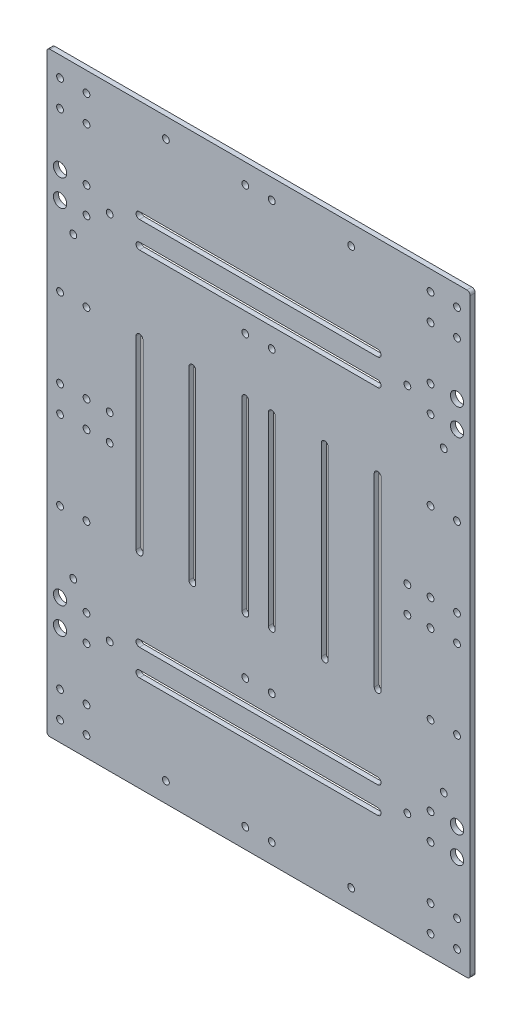
SolidWorks part; units mm, degrees
ref_plane "Front Plane" through (0, 0, 0) normal (0, 0, 1) x (1, 0, 0)
ref_plane "Top Plane" through (0, 0, 0) normal (0, 1, 0) x (1, 0, 0)
ref_plane "Right Plane" through (0, 0, 0) normal (1, 0, 0) x (0, 0, -1)
sketch "Sketch1" plane through (0, 0, 0) normal (0, 0, 1) x (1, 0, 0)
  line L1 (-128, -180) -> (128, -180)
  line L2 (-128, -180) -> (-128, 180)
  line L3 (-128, 180) -> (128, 180)
  line L4 (128, -180) -> (128, 180)
  line L5 (-128, -180) -> (128, 180) construction
  line L6 (-128, 180) -> (128, -180) construction
  point P0 (0, 0)
  dimension "D1" = 256
  dimension "D2" = 360
extrude "Boss-Extrude1" add sketch "Sketch1" along normal blind 3
fillet "Fillet1" radius 2 4 edges at (128, -180, 1.5) (-128, -180, 1.5) (-128, 180, 1.5) (128, 180, 1.5)
hole_wizard "Ø4.1 (4.1) Diameter Hole1" positions "Sketch3" profile "Sketch2" hole size "Ø4.1" standard "ANSI Metric" end condition through all
sketch "Sketch3" plane through (0, 0, 3) normal (0, 0, 1) x (1, 0, 0)
  point P0 (90, 8)
  point P2 (120, 8)
  point P4 (104, 8)
  point P9 (104, 56)
  point P11 (120, 56)
  point P13 (104, 104)
  point P15 (112, 90.15)
  point P17 (104, 120)
  point P19 (90, 112)
  point P21 (104, 152)
  point P23 (120, 152)
  point P25 (120, 168)
  point P27 (104, 168)
  point P37 (8, 168)
  point P39 (56, 168)
  point P47 (8, 90.15)
  dimension "D1" = 90
  dimension "D2" = 120
  dimension "D3" = 104
  dimension "D4" = 8
  dimension "D5" = 56
  dimension "D6" = 112
  dimension "D7" = 90.15
  dimension "D8" = 112
  dimension "D9" = 104
  dimension "D10" = 120
  dimension "D11" = 152
  dimension "D12" = 168
  dimension "D13" = 8
  dimension "D14" = 56
sketch "Sketch2" plane through (90, 8, 3) normal (1, 0, 0) x (0, -1, 0)
  line L0 (0, 0) -> (0, 3)
  line L1 (0, 3) -> (2.05, 3)
  line L2 (2.05, 3) -> (2.05, 0)
  line L5 (2.05, 0) -> (0, 0)
  line L11 (0, -6.35) -> (0, 107.95) construction
  dimension "Thru Hole Dia." = 4.1
  dimension "Thru Hole Depth" = 3
hole_wizard "Ø8.0 (8) Diameter Hole1" positions "Sketch5" profile "Sketch4" hole size "Ø8.0" standard "ANSI Metric" end condition through all
sketch "Sketch5" plane through (0, 0, 3) normal (0, 0, 1) x (1, 0, 0)
  point P0 (120, 120)
  point P2 (120, 104)
  dimension "D1" = 104
  dimension "D2" = 120
  dimension "D3" = 120
sketch "Sketch4" plane through (120, 120, 3) normal (1, 0, 0) x (0, -1, 0)
  line L0 (0, 0) -> (0, 3)
  line L1 (0, 3) -> (4, 3)
  line L2 (4, 3) -> (4, 0)
  line L5 (4, 0) -> (0, 0)
  line L11 (0, -6.35) -> (0, 107.95) construction
  dimension "Thru Hole Dia." = 8
  dimension "Thru Hole Depth" = 3
sketch "Sketch9" plane through (0, 0, 3) normal (0, 0, 1) x (1, 0, 0)
  line L0 (0, 104) -> (72, 104) construction
  line L1 (0, 106.05) -> (72, 106.05)
  line L2 (0, 101.95) -> (72, 101.95)
  line L3 (0, 120) -> (72, 120) construction
  line L4 (0, 122.05) -> (72, 122.05)
  line L5 (0, 117.95) -> (72, 117.95)
  line L6 (8, -56) -> (8, 56) construction
  line L7 (5.95, -56) -> (5.95, 56)
  line L8 (10.05, -56) -> (10.05, 56)
  line L9 (40, -56) -> (40, 56) construction
  line L10 (37.95, -56) -> (37.95, 56)
  line L11 (42.05, -56) -> (42.05, 56)
  line L12 (72, -56) -> (72, 56) construction
  line L13 (69.95, -56) -> (69.95, 56)
  line L14 (74.05, -56) -> (74.05, 56)
  line L16 (0, 122.05) -> (0, 117.95)
  line L17 (0, 106.05) -> (0, 101.95)
  arc A1 (72, 101.95) -> (72, 106.05) centre (72, 104) ccw
  arc A3 (72, 117.95) -> (72, 122.05) centre (72, 120) ccw
  arc A4 (5.95, -56) -> (10.05, -56) centre (8, -56) ccw
  arc A5 (10.05, 56) -> (5.95, 56) centre (8, 56) ccw
  arc A6 (37.95, -56) -> (42.05, -56) centre (40, -56) ccw
  arc A7 (42.05, 56) -> (37.95, 56) centre (40, 56) ccw
  arc A8 (69.95, -56) -> (74.05, -56) centre (72, -56) ccw
  arc A9 (74.05, 56) -> (69.95, 56) centre (72, 56) ccw
  point P2 (0, 104)
  point P9 (0, 120)
  point P16 (8, 0)
  point P22 (40, 0)
  point P29 (72, 0)
  dimension "D16" = 2.05
  dimension "D17" = 2.05
  dimension "D1" = 4.1
  dimension "D2" = 72
  dimension "D3" = 4.1
  dimension "D4" = 72
  dimension "D5" = 4.1
  dimension "D6" = 112
  dimension "D7" = 4.1
  dimension "D8" = 4.1
  dimension "D9" = 112
  dimension "D10" = 112
  dimension "D11" = 104
  dimension "D12" = 120
  dimension "D13" = 8
  dimension "D14" = 40
  dimension "D15" = 72
extrude "Cut-Extrude1" cut sketch "Sketch9" against normal through all
mirror "Mirror1" about plane through (0, 0, 0) normal (0, 1, 0) of "Cut-Extrude1", "Ø4.1 (4.1) Diameter Hole1", "Ø8.0 (8) Diameter Hole1"
mirror "Mirror2" about plane through (0, 0, 0) normal (1, 0, 0) of "Mirror1", "Ø4.1 (4.1) Diameter Hole1", "Ø8.0 (8) Diameter Hole1", "Cut-Extrude1"
